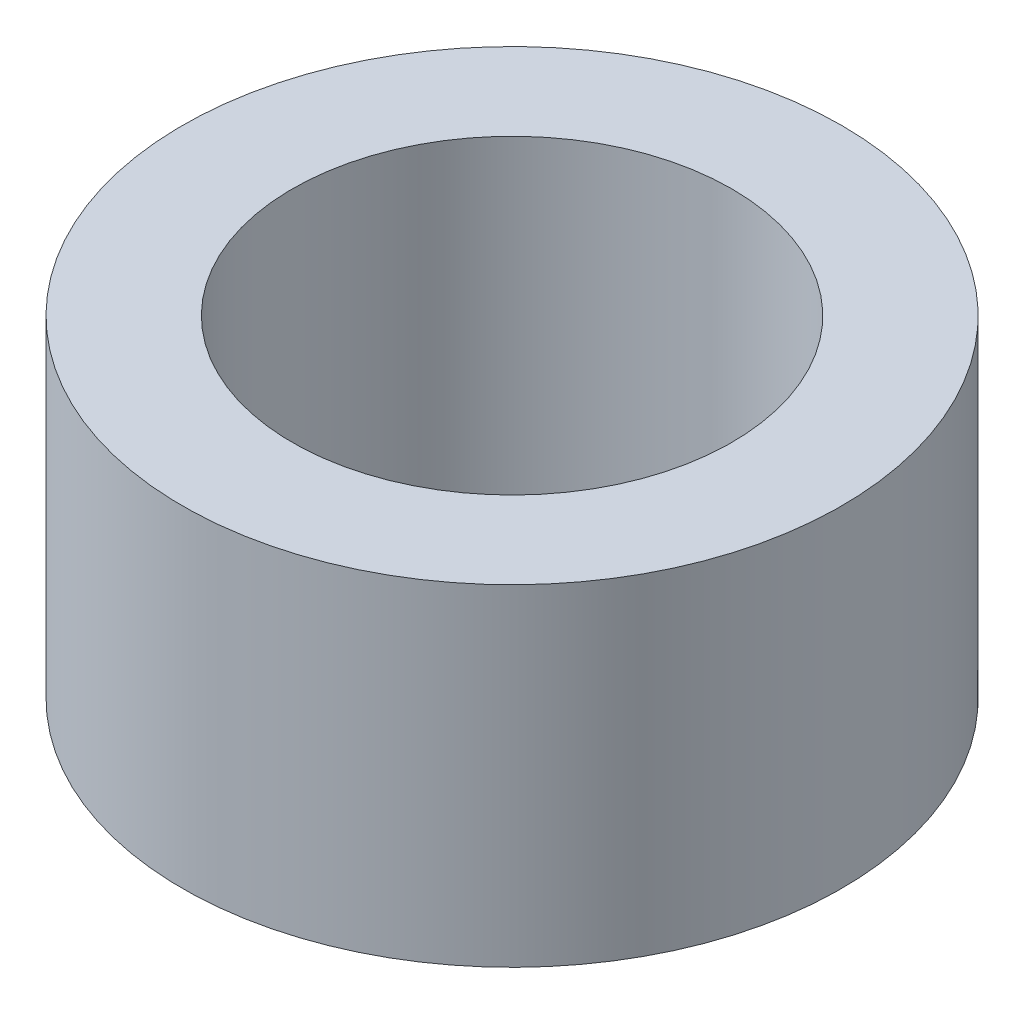
SolidWorks part; units mm, degrees
material "ABS"
ref_plane "Front Plane" through (0, 0, 0) normal (0, 0, 1) x (1, 0, 0)
ref_plane "Top Plane" through (0, 0, 0) normal (0, 1, 0) x (1, 0, 0)
ref_plane "Right Plane" through (0, 0, 0) normal (1, 0, 0) x (0, 0, -1)
sketch "Sketch1" plane through (0, 0, 0) normal (0, 1, 0) x (1, 0, 0)
  circle A0 centre (0, 0) radius 6
  circle A1 centre (0, 0) radius 4
  dimension "D1" = 8
  dimension "D2" = 12
extrude "Boss-Extrude1" add sketch "Sketch1" along normal blind 6.0325
